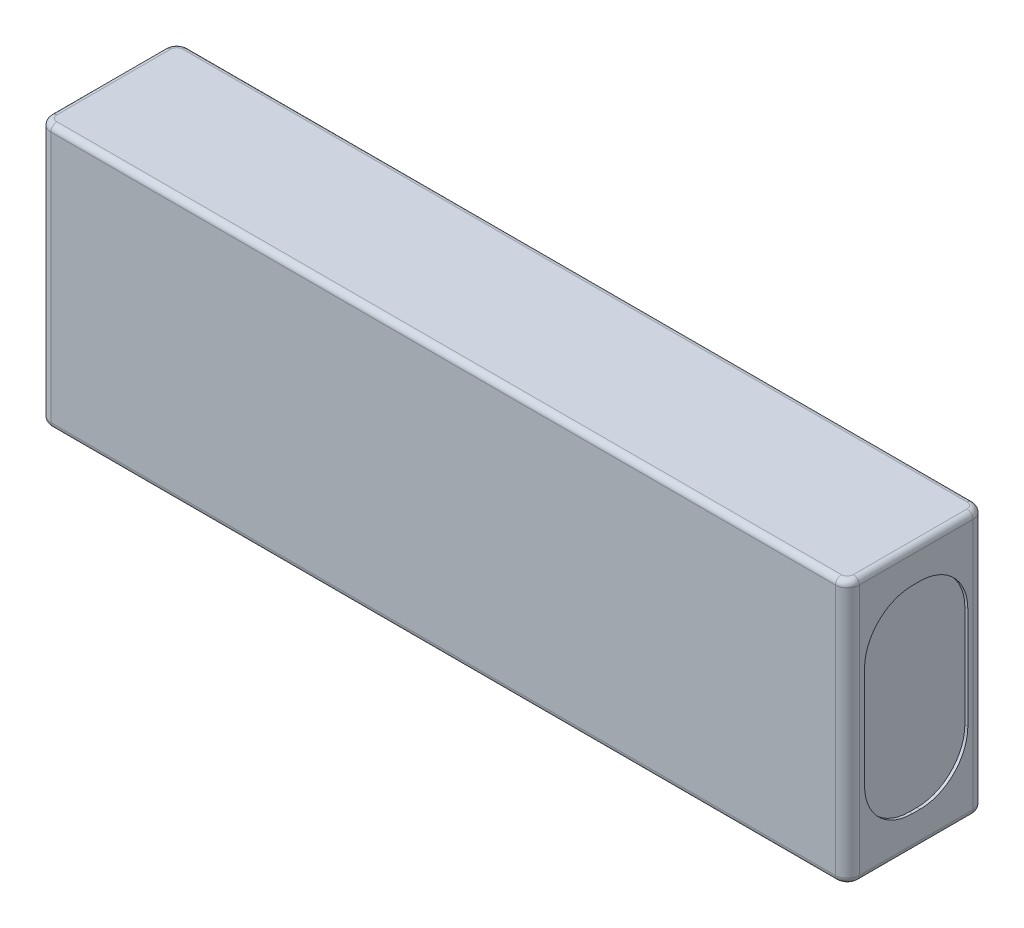
SolidWorks part; units mm, degrees
ref_plane "Front Plane" through (0, 0, 0) normal (0, 0, 1) x (1, 0, 0)
ref_plane "Top Plane" through (0, 0, 0) normal (0, 1, 0) x (1, 0, 0)
ref_plane "Right Plane" through (0, 0, 0) normal (1, 0, 0) x (0, 0, -1)
ref_plane "Plane1" through (0, 0, -15) normal (0, 0, -1) x (-1, 0, 0)
sketch "Sketch1" plane through (0, 0, -15) normal (0, 0, -1) x (-1, 0, 0)
  line L0 (-69, -22) -> (66, -22)
  line L1 (66, -22) -> (66, 22)
  line L2 (66, 22) -> (-69, 22)
  line L3 (-69, 22) -> (-69, -22)
  line L4 (-69, 0) -> (66, 0) construction
  line L5 (-1.5, 22) -> (-1.5, -22) construction
  dimension "D1" = 44
  dimension "D2" = 135
extrude "Boss-Extrude1" add sketch "Sketch1" against normal blind 23
sketch "Sketch2" plane through (69, 0, 0) normal (1, 0, 0) x (0, 0, -1)
  line L0 (-5.125, 8.5) -> (-5.125, -8.5)
  line L1 (2.875, -16.5) -> (4.125, -16.5)
  line L2 (12.125, -8.5) -> (12.125, 8.5)
  line L3 (4.125, 16.5) -> (2.875, 16.5)
  line L4 (-8, 22) -> (15, -22) construction
  line L5 (15, 22) -> (-8, -22) construction
  line L6 (-5.125, 16.5) -> (12.125, -16.5) construction
  line L7 (12.125, 16.5) -> (-5.125, -16.5) construction
  line L12 (-8, 22) -> (15, 22) construction
  line L13 (-8, 22) -> (-8, -22) construction
  line L14 (-8, -22) -> (15, -22) construction
  line L15 (15, 22) -> (15, -22) construction
  line L16 (-8, 22) -> (15, -22) construction
  line L17 (-8, -22) -> (15, 22) construction
  arc A0 (-5.125, -8.5) -> (2.875, -16.5) centre (2.875, -8.5) ccw
  arc A1 (4.125, -16.5) -> (12.125, -8.5) centre (4.125, -8.5) ccw
  arc A2 (12.125, 8.5) -> (4.125, 16.5) centre (4.125, 8.5) ccw
  arc A3 (-5.125, 8.5) -> (2.875, 16.5) centre (2.875, 8.5) cw
  point P16 (3.5, 0)
  dimension "D3" = 8
  dimension "D1" = 17.25
  dimension "D2" = 23
extrude "Cut-Extrude1" cut sketch "Sketch2" against normal blind 0.5
sketch "Sketch3" plane through (-66, 0, 0) normal (-1, 0, 0) x (0, 0, 1)
  line L0 (-2.875, 16.5) -> (-4.125, 16.5)
  line L1 (-12.125, 8.5) -> (-12.125, -8.5)
  line L2 (-4.125, -16.5) -> (-2.875, -16.5)
  line L3 (5.125, -8.5) -> (5.125, 8.5)
  line L4 (-12.125, 16.5) -> (5.125, -16.5) construction
  line L5 (5.125, 16.5) -> (-12.125, -16.5) construction
  line L6 (-15, 22) -> (8, -22) construction
  line L7 (8, -22) -> (-15, -22) construction
  line L8 (-15, -22) -> (8, 22) construction
  arc A0 (-12.125, -8.5) -> (-4.125, -16.5) centre (-4.125, -8.5) ccw
  arc A1 (-2.875, -16.5) -> (5.125, -8.5) centre (-2.875, -8.5) ccw
  arc A2 (-2.875, 16.5) -> (5.125, 8.5) centre (-2.875, 8.5) cw
  arc A3 (-4.125, 16.5) -> (-12.125, 8.5) centre (-4.125, 8.5) ccw
  dimension "D3" = 8
  dimension "D1" = 17.25
  dimension "D2" = 23
extrude "Cut-Extrude2" cut sketch "Sketch3" against normal blind 0.5
fillet "Fillet1" radius 2 4 edges at (-66, 0, -15) (-66, 0, 8) (69, 0, -15) (69, 0, 8)
fillet "Fillet2" radius 1 16 edges at (68.4142, 22, -14.4142) (69, 22, -3.5) (1.5, 22, -15) (68.4142, 22, 7.4142) (-65.4142, 22, -14.4142) (1.5, 22, 8) (-66, 22, -3.5) (-65.4142, 22, 7.4142) (-66, -22, -3.5) (-65.4142, -22, -14.4142) (-65.4142, -22, 7.4142) (1.5, -22, -15) (1.5, -22, 8) (68.4142, -22, -14.4142) (68.4142, -22, 7.4142) (69, -22, -3.5)
equation "\"D1@Sketch3\"=\"D2@Sketch3\" * .75"
equation "\"D1@Sketch2\"=\"D2@Sketch2\"* .75"
